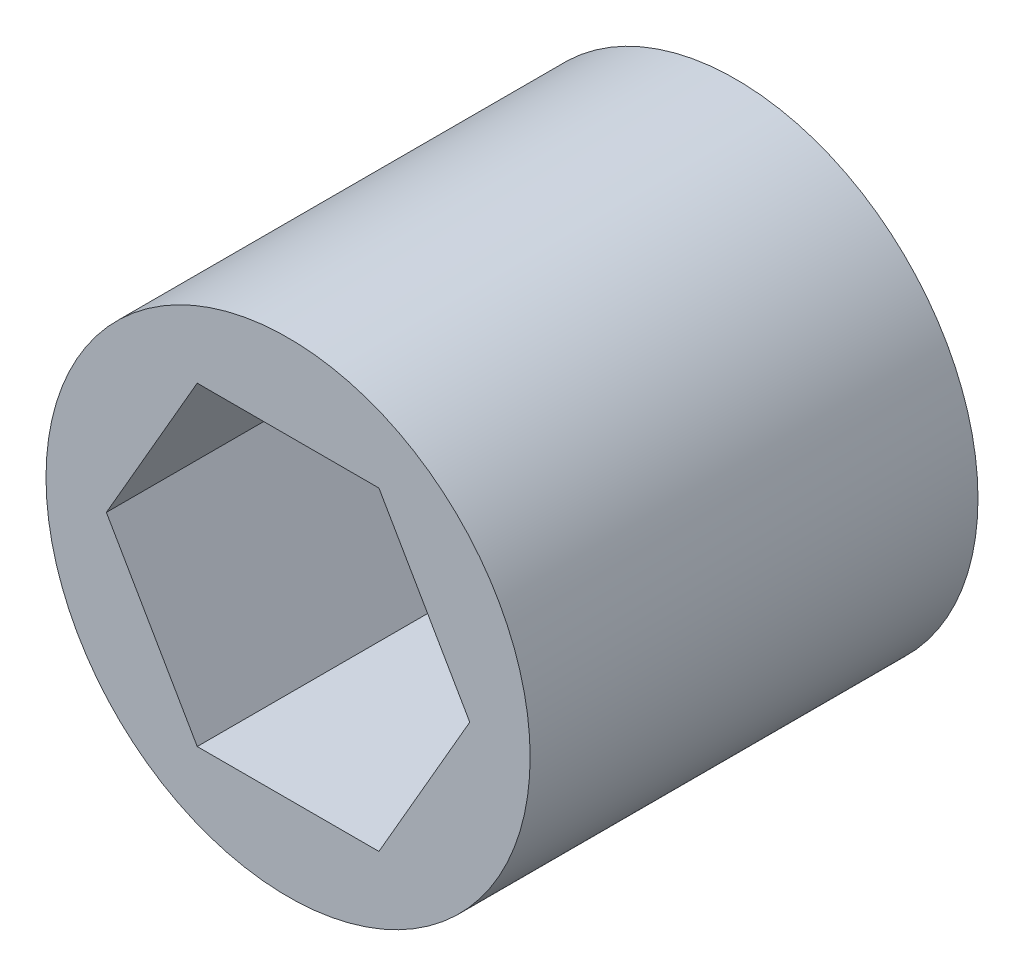
SolidWorks part; units mm, degrees
material "Nylon 101"
ref_plane "Front" through (0, 0, 0) normal (0, 0, 1) x (1, 0, 0)
ref_plane "Top" through (0, 0, 0) normal (0, 1, 0) x (1, 0, 0)
ref_plane "Right" through (0, 0, 0) normal (1, 0, 0) x (0, 0, -1)
sketch "Sketch1" plane through (0, 0, 0) normal (0, 0, 1) x (1, 0, 0)
  line L1 (1.5011, 0) -> (0.7506, 1.3)
  line L2 (0.7506, 1.3) -> (-0.7506, 1.3)
  line L3 (-0.7506, 1.3) -> (-1.5011, 0)
  line L4 (-1.5011, 0) -> (-0.7506, -1.3)
  line L5 (-0.7506, -1.3) -> (0.7506, -1.3)
  line L6 (0.7506, -1.3) -> (1.5011, 0)
  circle A0 centre (0, 0) radius 2
  circle A1 centre (0, 0) radius 1.3 construction
  dimension "D1" = 2.6
  dimension "D2" = 4
extrude "Boss-Extrude1_ShaftSocket" add sketch "Sketch1" along normal mid plane 3.7
